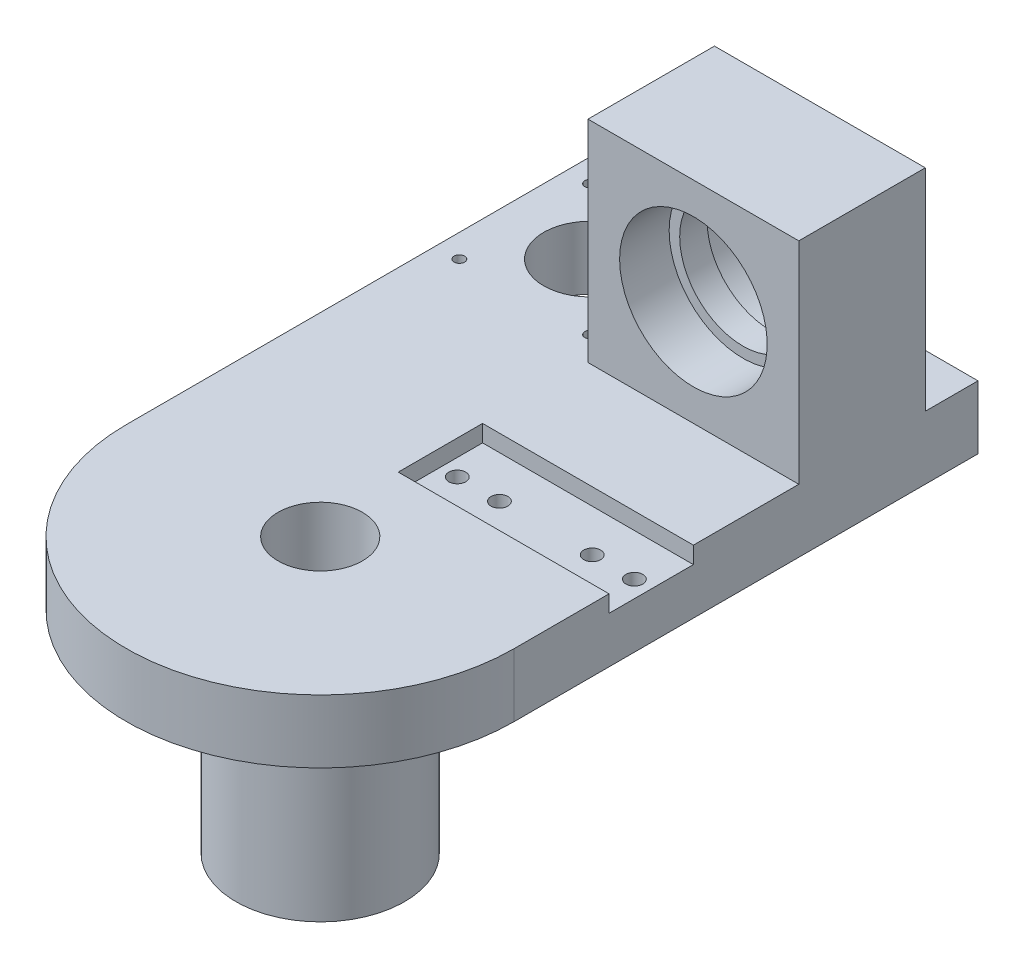
SolidWorks part; units mm, degrees
ref_plane "Ebene vorne" through (0, 0, 0) normal (0, 0, 1) x (1, 0, 0)
ref_plane "Ebene oben" through (0, 0, 0) normal (0, 1, 0) x (1, 0, 0)
ref_plane "Ebene rechts" through (0, 0, 0) normal (1, 0, 0) x (0, 0, -1)
sketch "Skizze1" plane through (0, 0, 0) normal (0, 1, 0) x (1, 0, 0)
  line L0 (-25.9794, -46) -> (25.9794, -46) construction
  line L1 (-46, 0) -> (46, 0)
  line L2 (-46, 0) -> (-46, 110)
  line L3 (-46, 110) -> (46, 110)
  line L4 (46, 0) -> (46, 110)
  line L5 (-46, 0) -> (46, 110) construction
  line L6 (-46, 110) -> (46, 0) construction
  line L8 (-46, 110) -> (-4, 110)
  line L9 (-46, 110) -> (-46, 68)
  line L10 (-46, 68) -> (-4, 68)
  line L11 (-4, 110) -> (-4, 68)
  line L12 (-46, 110) -> (-4, 68) construction
  line L13 (-46, 68) -> (-4, 110) construction
  circle A0 centre (0, 0) radius 46
  circle A1 centre (-25, 89) radius 11
  circle A2 centre (-40.5, 104.5) radius 1.25
  circle A3 centre (-9.5, 104.5) radius 1.25
  circle A4 centre (-9.5, 73.5) radius 1.25
  circle A5 centre (-40.5, 73.5) radius 1.25
  point P7 (0, 55)
  point P11 (0, -46)
  point P14 (-25, 89)
  dimension "D1" = 92
  dimension "D2" = 42
  dimension "D3" = 156
  dimension "D4" = 42
extrude "Aufsatz-Linear austragen1" add sketch "Skizze1" along normal blind 15 contours A1 A0 L11 L3 L2 L10 | A1 A0 L10 L11 | A0 L10 L2 | L1 A0 L11 L10 | L1 A0 | A0 L4 L3 L11
sketch "Skizze2" plane through (0, 15, 0) normal (0, 1, 0) x (1, 0, 0)
  line L0 (-46, 110) -> (46, 110) construction
  line L1 (46, 97.5) -> (-4, 97.5)
  line L2 (46, 97.5) -> (46, 67.5)
  line L3 (46, 67.5) -> (-4, 67.5)
  line L4 (-4, 97.5) -> (-4, 67.5)
  line L5 (46, 97.5) -> (-4, 67.5) construction
  line L6 (46, 67.5) -> (-4, 97.5) construction
  point P4 (21, 82.5)
  dimension "D1" = 50
  dimension "D2" = 30
  dimension "D3" = 12.5
extrude "Aufsatz-Linear austragen2" add sketch "Skizze2" along normal blind 50
sketch "Skizze3" plane through (0, 0, -97.5) normal (0, 0, -1) x (-1, 0, 0)
  line L5 (-46, 65) -> (4, 65)
  line L6 (-46, 65) -> (-46, 15)
  line L7 (-46, 15) -> (4, 15)
  line L8 (4, 65) -> (4, 15)
  line L9 (-46, 65) -> (4, 15) construction
  line L10 (-46, 15) -> (4, 65) construction
  circle A1 centre (-21, 40) radius 15
  point P4 (-21, 40)
extrude "Schnitt-Linear austragen9" cut sketch "Skizze3" against normal blind 30 contours A1
sketch "Skizze4" plane through (0, 0, -97.5) normal (0, 0, -1) x (-1, 0, 0)
  line L5 (-46, 65) -> (4, 65)
  line L6 (-46, 65) -> (-46, 15)
  line L7 (-46, 15) -> (4, 15)
  line L8 (4, 65) -> (4, 15)
  line L9 (-46, 65) -> (4, 15) construction
  line L10 (-46, 15) -> (4, 65) construction
  circle A1 centre (-21, 40) radius 17.5
  point P4 (-21, 40)
  dimension "D1" = 35
extrude "Schnitt-Linear austragen10" cut sketch "Skizze4" against normal blind 11.75 contours A1
ref_plane "Ebene1" through (0, 0, -82.5) normal (0, 0, -1) x (-1, 0, 0)
sketch "Skizze5" plane through (0, 15, 0) normal (0, 1, 0) x (1, 0, 0)
  line L0 (46, 0) -> (46, 67.5) construction
  line L1 (-4, 67.5) -> (46, 67.5)
  line L2 (-4, 67.5) -> (-4, 42.5)
  line L3 (-4, 42.5) -> (46, 42.5)
  line L4 (46, 67.5) -> (46, 42.5)
  line L5 (-4, 67.5) -> (46, 42.5) construction
  line L6 (-4, 42.5) -> (46, 67.5) construction
  line L8 (-4, 42.5) -> (46, 42.5)
  line L9 (-4, 42.5) -> (-4, 22.5)
  line L10 (-4, 22.5) -> (46, 22.5)
  line L11 (46, 42.5) -> (46, 22.5)
  line L12 (-4, 42.5) -> (46, 22.5) construction
  line L13 (-4, 22.5) -> (46, 42.5) construction
  point P4 (21, 55)
  point P10 (21, 32.5)
  line M7 (46, 0) -> (46, 67.5)
  dimension "D1" = 20
  dimension "D2" = 25
extrude "Schnitt-Linear austragen3" cut sketch "Skizze5" against normal blind 4 contours L9 L10 L3 M7
sketch "Skizze6" plane through (0, 11, 0) normal (0, 1, 0) x (1, 0, 0)
  line L0 (-4, 32.5) -> (46, 32.5) construction
  line L1 (-4, 42.5) -> (-4, 22.5) construction
  line L2 (46, 22.5) -> (46, 42.5) construction
  line L3 (21, 32.5) -> (21, 14.5298) construction
  circle A0 centre (0, 32.5) radius 2
  circle A1 centre (42, 32.5) radius 2
  circle A2 centre (10, 32.5) radius 2
  circle A3 centre (32, 32.5) radius 2
  dimension "D2" = 4
  dimension "D3" = 4
  dimension "D1" = 4
  dimension "D4" = 10
extrude "Schnitt-Linear austragen4" cut sketch "Skizze6" against normal blind 11
sketch "Skizze8" plane through (0, 0, 0) normal (0, -1, 0) x (1, 0, 0)
  circle A0 centre (0, 0) radius 20
  circle A1 centre (0, 0) radius 32.5
  circle A2 centre (0, 0) radius 26.25
  dimension "D1" = 40
  dimension "D2" = 65
  dimension "D3" = 52.5
extrude "Schnitt-Linear austragen5" cut sketch "Skizze8" against normal blind 4 contours A1 A2
sketch "Skizze10" plane through (0, 0, 0) normal (0, -1, 0) x (1, 0, 0)
  circle A0 centre (0, 0) radius 20
extrude "Aufsatz-Linear austragen3" add sketch "Skizze10" along normal blind 50 contours A0
sketch "Skizze11" plane through (0, 0, 0) normal (0, -1, 0) x (1, 0, 0)
  circle A0 centre (0, -32.5) radius 3.5
  circle A1 centre (10, -32.5) radius 3.5
  circle A2 centre (32, -32.5) radius 3.5
  circle A3 centre (42, -32.5) radius 3.5
  dimension "D1" = 7
  dimension "D2" = 7
extrude "Schnitt-Linear austragen6" cut sketch "Skizze11" against normal offset from surface (8 mm away) 8 up to face at (0, 0, -20)
sketch "Skizze12" plane through (0, -50, 0) normal (0, -1, 0) x (1, 0, 0)
  circle A0 centre (0, 0) radius 10
  circle A1 centre (0, 0) radius 20 construction
  dimension "D1" = 10
extrude "Schnitt-Linear austragen7" cut sketch "Skizze12" against normal blind 65
sketch "Skizze13" plane through (0, -50, 0) normal (0, -1, 0) x (1, 0, 0)
  line L0 (10, 0) -> (20, 0) construction
  circle A0 centre (0, 0) radius 10 construction
  circle A1 centre (0, 0) radius 20 construction
  circle A3 centre (15, 0) radius 2
  circle A4 centre (7.5, -12.9904) radius 2
  circle A5 centre (-7.5, -12.9904) radius 2
  circle A6 centre (-15, 0) radius 2
  circle A7 centre (-7.5, 12.9904) radius 2
  circle A8 centre (7.5, 12.9904) radius 2
  point P21 (0, 0)
  dimension "D1" = 6
extrude "Schnitt-Linear austragen8" cut sketch "Skizze13" against normal blind 15
mirror "Spiegeln2" about plane through (0, 0, -82.5) normal (0, 0, -1) of "Schnitt-Linear austragen10"
